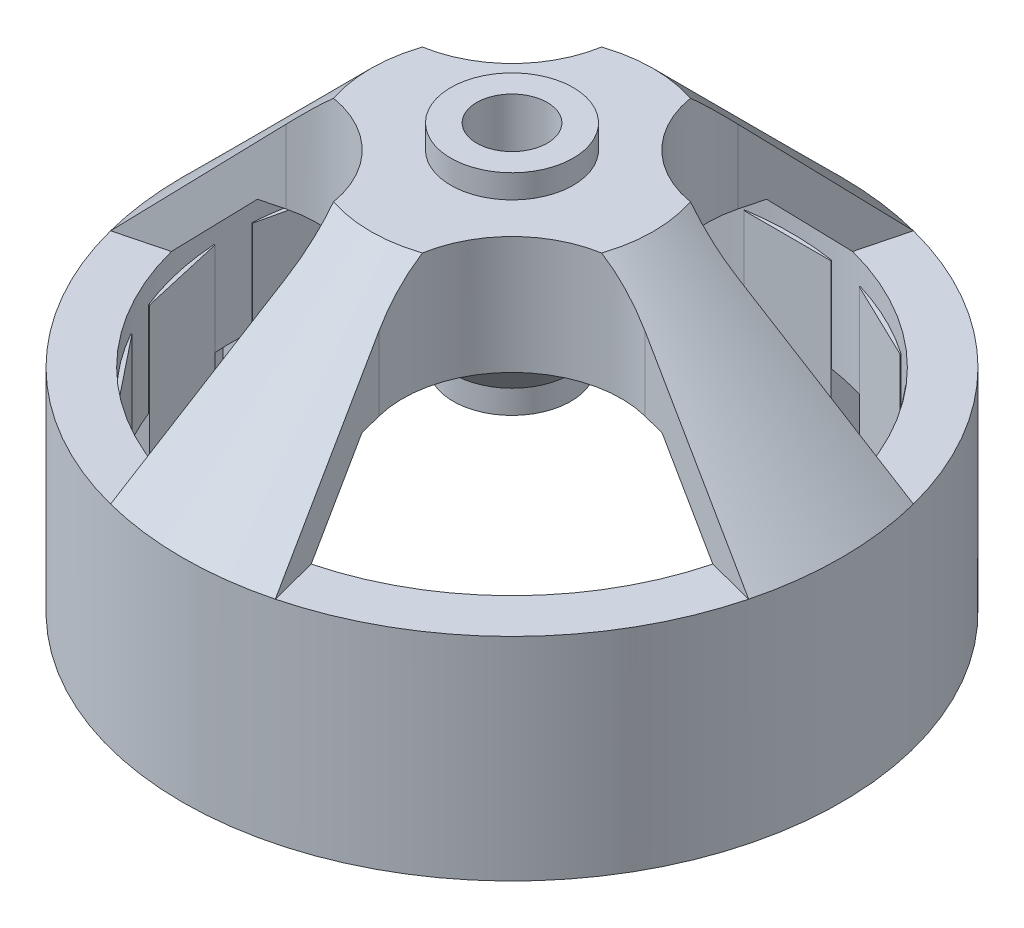
SolidWorks part; units mm, degrees
ref_plane "Front Plane" through (0, 0, 0) normal (0, 0, 1) x (1, 0, 0)
ref_plane "Top Plane" through (0, 0, 0) normal (0, 1, 0) x (1, 0, 0)
ref_plane "Right Plane" through (0, 0, 0) normal (1, 0, 0) x (0, 0, -1)
sketch "Sketch1" plane through (0, 0, 0) normal (0, 0, 1) x (1, 0, 0)
  line L0 (0, 0) -> (0, 18) construction
  line L1 (14, 0) -> (14, 9)
  line L2 (14, 9) -> (6, 17)
  line L3 (6, 17) -> (2.6, 17)
  line L4 (2.6, 17) -> (2.6, 18)
  line L5 (2.6, 18) -> (1.5, 18)
  line L6 (1.5, 18) -> (1.5, 9)
  line L7 (14, 0) -> (13.5, 0)
  line L8 (1.5, 9) -> (2.5, 9)
  line L9 (2.5, 9) -> (2.5, 10)
  line L10 (2.5, 10) -> (4.5, 12)
  line L11 (4.5, 12) -> (8.8787, 12)
  line L12 (8.8787, 12) -> (13.5, 7.3787)
  line L13 (13.5, 7.3787) -> (13.5, 0)
  dimension "D1" = 18
  dimension "D2" = 1
  dimension "D3" = 0.5
  dimension "D4" = 5.2
  dimension "D5" = 3
  dimension "D6" = 12
  dimension "D7" = 9
  dimension "D8" = 9
  dimension "D9" = 1.5
  dimension "D10" = 5
  dimension "D11" = 28
  dimension "D12" = 1
revolve "Revolve1" add sketch "Sketch1" angle 360 about L0
sketch "Sketch2" plane through (0, 17, 0) normal (0, 1, 0) x (1, 0, 0)
  line L0 (0, 0) -> (0, 14) construction
  line L1 (0, 0) -> (14, 0) construction
  line L2 (3.5, 13.5554) -> (1.9692, 7.6268)
  line L3 (13.5554, 3.5) -> (7.6268, 1.9692)
  line L4 (0, 0) -> (6.4658, 6.4658) construction
  line L5 (13.5554, -3.5) -> (7.6268, -1.9692)
  line L6 (3.5, -13.5554) -> (1.9692, -7.6268)
  line L7 (-3.5, -13.5554) -> (-1.9692, -7.6268)
  line L8 (-13.5554, -3.5) -> (-7.6268, -1.9692)
  line L9 (-13.5554, 3.5) -> (-7.6268, 1.9692)
  line L10 (-3.5, 13.5554) -> (-1.9692, 7.6268)
  circle A0 centre (0, 0) radius 14 construction
  arc A1 (1.9692, 7.6268) -> (7.6268, 1.9692) centre (6.4658, 6.4658) ccw
  circle A2 centre (0, 0) radius 4.5 construction
  arc A3 (3.5, 13.5554) -> (13.5554, 3.5) centre (0, 0) cw
  arc A4 (13.5554, -3.5) -> (3.5, -13.5554) centre (0, 0) cw
  arc A5 (7.6268, -1.9692) -> (1.9692, -7.6268) centre (6.4658, -6.4658) ccw
  arc A6 (-3.5, -13.5554) -> (-13.5554, -3.5) centre (0, 0) cw
  arc A7 (-1.9692, -7.6268) -> (-7.6268, -1.9692) centre (-6.4658, -6.4658) ccw
  arc A8 (-13.5554, 3.5) -> (-3.5, 13.5554) centre (0, 0) cw
  arc A9 (-7.6268, 1.9692) -> (-1.9692, 7.6268) centre (-6.4658, 6.4658) ccw
  point P11 (3.182, 3.182)
  point P32 (0, 0)
  dimension "D1" = 45
  dimension "D2" = 7
  dimension "D3" = 4
extrude "Cut-Extrude1" cut sketch "Sketch2" against normal up to surface (8 mm away) up to face at (0, 9, -2.5)
sketch "Sketch5" plane through (0, 9, 0) normal (0, 1, 0) x (1, 0, 0)
  circle A0 centre (0, 0) radius 14
  circle A1 centre (0, 0) radius 11.8787
  arc A2 (-13.5554, -3.5) -> (-3.5, -13.5554) centre (0, 0) ccw construction
  arc A3 (-11.5015, -2.9697) -> (-2.9697, -11.5015) centre (0, 0) ccw construction
extrude "Boss-Extrude2" add sketch "Sketch5" against normal offset from surface (5 mm away) 4 up to face at (0, 0, -14)
sketch "Sketch3" plane through (0, 0, 0) normal (0, -1, 0) x (1, 0, 0)
  line L0 (0, 0) -> (0, 13.5) construction
  line L1 (-1.85, 11.7) -> (1.85, 11.7)
  line L2 (-1.85, 11.7) -> (-1.85, 13.5)
  line L3 (-1.85, 13.5) -> (1.85, 13.5)
  line L4 (1.85, 11.7) -> (1.85, 13.5)
  line L5 (3.4096, 11.344) -> (6.7432, 9.7387)
  line L6 (3.4096, 11.344) -> (4.1906, 12.9658)
  line L7 (4.1906, 12.9658) -> (7.5242, 11.3604)
  line L8 (6.7432, 9.7387) -> (7.5242, 11.3604)
  line L9 (7.994, 8.7412) -> (10.3009, 5.8484)
  line L10 (7.994, 8.7412) -> (9.4013, 9.8635)
  line L11 (9.4013, 9.8635) -> (11.7082, 6.9707)
  line L12 (10.3009, 5.8484) -> (11.7082, 6.9707)
  line L13 (10.995, 4.4071) -> (11.8183, 0.7999)
  line L14 (10.995, 4.4071) -> (12.7499, 4.8076)
  line L15 (12.7499, 4.8076) -> (13.5732, 1.2004)
  line L16 (11.8183, 0.7999) -> (13.5732, 1.2004)
  line L17 (11.8183, -0.7999) -> (10.995, -4.4071)
  line L18 (11.8183, -0.7999) -> (13.5732, -1.2004)
  line L19 (13.5732, -1.2004) -> (12.7499, -4.8076)
  line L20 (10.995, -4.4071) -> (12.7499, -4.8076)
  line L21 (10.3009, -5.8484) -> (7.994, -8.7412)
  line L22 (10.3009, -5.8484) -> (11.7082, -6.9707)
  line L23 (11.7082, -6.9707) -> (9.4013, -9.8635)
  line L24 (7.994, -8.7412) -> (9.4013, -9.8635)
  line L25 (6.7432, -9.7387) -> (3.4096, -11.344)
  line L26 (6.7432, -9.7387) -> (7.5242, -11.3604)
  line L27 (7.5242, -11.3604) -> (4.1906, -12.9658)
  line L28 (3.4096, -11.344) -> (4.1906, -12.9658)
  line L29 (1.85, -11.7) -> (-1.85, -11.7)
  line L30 (1.85, -11.7) -> (1.85, -13.5)
  line L31 (1.85, -13.5) -> (-1.85, -13.5)
  line L32 (-1.85, -11.7) -> (-1.85, -13.5)
  line L33 (-3.4096, -11.344) -> (-6.7432, -9.7387)
  line L34 (-3.4096, -11.344) -> (-4.1906, -12.9658)
  line L35 (-4.1906, -12.9658) -> (-7.5242, -11.3604)
  line L36 (-6.7432, -9.7387) -> (-7.5242, -11.3604)
  line L37 (-7.994, -8.7412) -> (-10.3009, -5.8484)
  line L38 (-7.994, -8.7412) -> (-9.4013, -9.8635)
  line L39 (-9.4013, -9.8635) -> (-11.7082, -6.9707)
  line L40 (-10.3009, -5.8484) -> (-11.7082, -6.9707)
  line L41 (-10.995, -4.4071) -> (-11.8183, -0.7999)
  line L42 (-10.995, -4.4071) -> (-12.7499, -4.8076)
  line L43 (-12.7499, -4.8076) -> (-13.5732, -1.2004)
  line L44 (-11.8183, -0.7999) -> (-13.5732, -1.2004)
  line L45 (-11.8183, 0.7999) -> (-10.995, 4.4071)
  line L46 (-11.8183, 0.7999) -> (-13.5732, 1.2004)
  line L47 (-13.5732, 1.2004) -> (-12.7499, 4.8076)
  line L48 (-10.995, 4.4071) -> (-12.7499, 4.8076)
  line L49 (-10.3009, 5.8484) -> (-7.994, 8.7412)
  line L50 (-10.3009, 5.8484) -> (-11.7082, 6.9707)
  line L51 (-11.7082, 6.9707) -> (-9.4013, 9.8635)
  line L52 (-7.994, 8.7412) -> (-9.4013, 9.8635)
  line L53 (-6.7432, 9.7387) -> (-3.4096, 11.344)
  line L54 (-6.7432, 9.7387) -> (-7.5242, 11.3604)
  line L55 (-7.5242, 11.3604) -> (-4.1906, 12.9658)
  line L56 (-3.4096, 11.344) -> (-4.1906, 12.9658)
  circle A0 centre (0, 0) radius 13.5 construction
  point P64 (0, 0)
  dimension "D2" = 1.8
  dimension "D1" = 3.7
  dimension "D3" = 14
extrude "Boss-Extrude3" add sketch "Sketch3" against normal offset from surface (7 mm away) 1 from offset 1 up to face at (-8.5156, 9, -8.5156)
